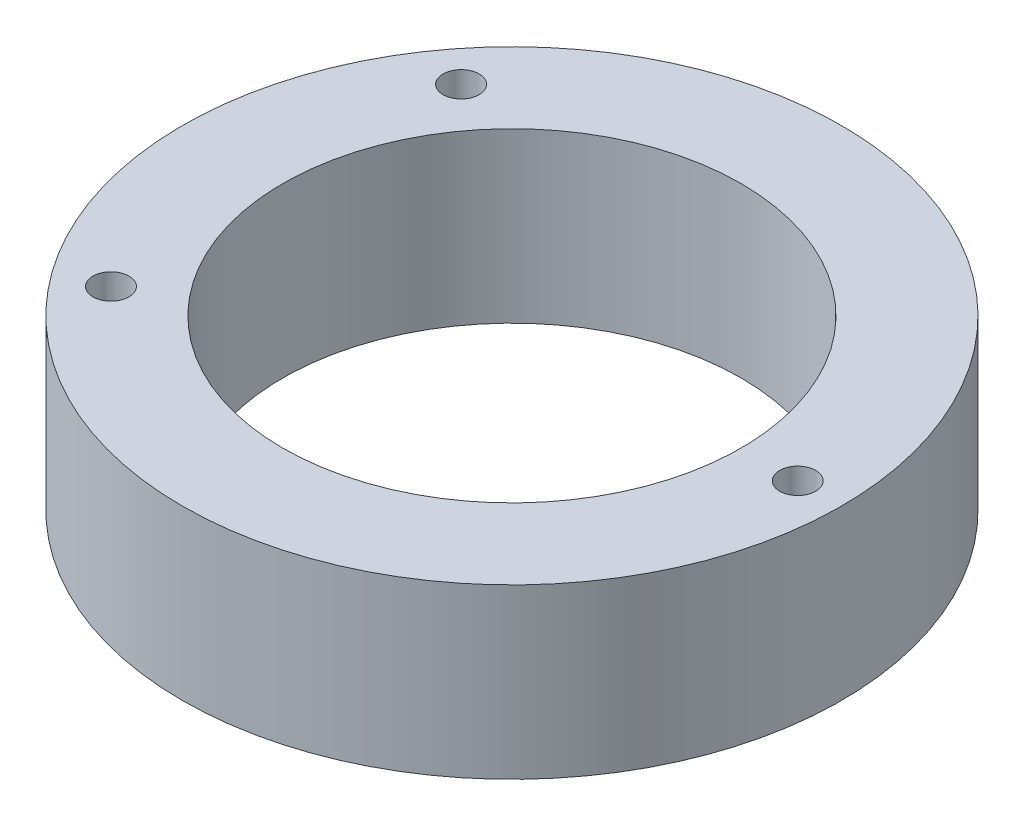
SolidWorks part; units mm, degrees
ref_plane "Front Plane" through (0, 0, 0) normal (0, 0, 1) x (1, 0, 0)
ref_plane "Top Plane" through (0, 0, 0) normal (0, 1, 0) x (1, 0, 0)
ref_plane "Right Plane" through (0, 0, 0) normal (1, 0, 0) x (0, 0, -1)
sketch "Sketch1" plane through (0, 0, 0) normal (0, 1, 0) x (1, 0, 0)
  line L0 (0, 0) -> (-21.9327, 17.0005) construction
  line L1 (0, 0) -> (-21.9327, -17.0005) construction
  line L2 (0, 0) -> (27.75, 0) construction
  line L3 (-21.9327, 17.0005) -> (-21.9327, -17.0005) construction
  circle A0 centre (0, 0) radius 22.25
  circle A1 centre (0, 0) radius 32
  circle A2 centre (27.75, 0) radius 1.75
  circle A3 centre (-21.9327, 17.0005) radius 1.75
  circle A4 centre (-21.9327, -17.0005) radius 1.75
  dimension "D1" = 44.5
  dimension "D2" = 64
  dimension "D5" = 3.5
  dimension "D3" = 75.56
  dimension "D4" = 27.75
extrude "Boss-Extrude1" add sketch "Sketch1" along normal blind 16.35
